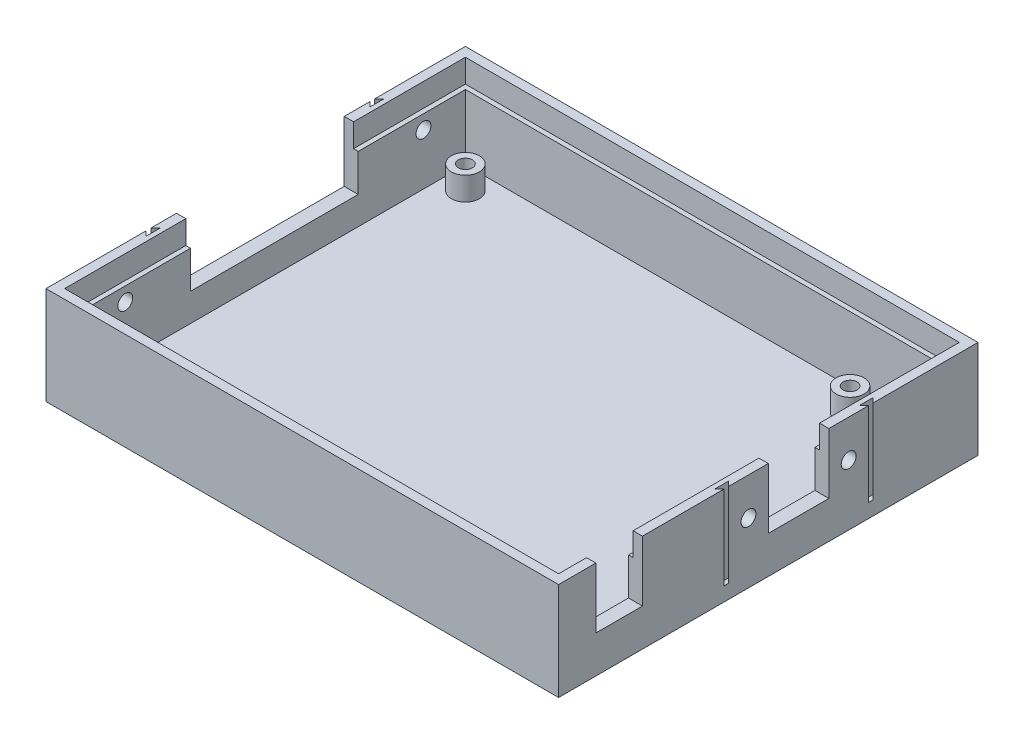
SolidWorks part; units mm, degrees
ref_plane "Alzado" through (0, 0, 0) normal (0, 0, 1) x (1, 0, 0)
ref_plane "Planta" through (0, 0, 0) normal (0, 1, 0) x (1, 0, 0)
ref_plane "Vista lateral" through (0, 0, 0) normal (1, 0, 0) x (0, 0, -1)
sketch "Croquis1" plane through (0, 0, 0) normal (0, 1, 0) x (1, 0, 0)
  line L1 (-51, -41) -> (51, -41) construction
  line L2 (-51, -41) -> (-51, 41) construction
  line L3 (-51, 41) -> (51, 41) construction
  line L4 (51, -41) -> (51, 41) construction
  line L5 (-51, -41) -> (51, 41) construction
  line L6 (-51, 41) -> (51, -41) construction
  line L7 (-55, -45) -> (55, -45)
  line L8 (-55, -45) -> (-55, 45)
  line L9 (-55, 45) -> (55, 45)
  line L10 (55, -45) -> (55, 45)
  line L11 (-55, -45) -> (55, 45) construction
  line L12 (-55, 45) -> (55, -45) construction
  point P0 (0, 0)
  point P6 (0, 0)
  dimension "D1" = 82
  dimension "D2" = 102
  dimension "D3" = 4
  dimension "D4" = 4
extrude "Saliente-Extruir1" add sketch "Croquis1" along normal blind 2
sketch "Croquis3" plane through (0, 2, 0) normal (0, 1, 0) x (1, 0, 0)
  line L0 (0, 0) -> (-51, 0) construction
  line L1 (-51, -41) -> (51, -41) construction
  line L2 (-51, -41) -> (-51, 41) construction
  line L3 (-51, 41) -> (51, 41) construction
  line L4 (51, -41) -> (51, 41) construction
  line L5 (-51, -41) -> (51, 41) construction
  line L6 (-51, 41) -> (51, -41) construction
  circle A0 centre (-47.19, -37.19) radius 3
  circle A1 centre (-47.19, 37.19) radius 3
  circle A2 centre (35.36, -37.19) radius 3
  circle A3 centre (35.36, 37.19) radius 3
  point P0 (0, 0)
  dimension "D3" = 6
  dimension "D4" = 3.81
  dimension "D5" = 3.81
  dimension "D6" = 6
  dimension "D7" = 86.36
  dimension "D8" = 3.81
  dimension "D1" = 82
  dimension "D2" = 102
extrude "Saliente-Extruir2" add sketch "Croquis3" along normal blind 5
sketch "Croquis4" plane through (0, 7, 0) normal (0, 1, 0) x (1, 0, 0)
  circle A0 centre (-47.19, -37.19) radius 1.5
  circle A1 centre (35.36, -37.19) radius 1.5
  circle A2 centre (35.36, 37.19) radius 1.5
  circle A3 centre (-47.19, 37.19) radius 1.5
  dimension "D1" = 3
  dimension "D2" = 3
  dimension "D3" = 3
  dimension "D4" = 3
extrude "Cortar-Extruir1" cut sketch "Croquis4" against normal blind 4
sketch "Croquis5" plane through (0, 2, 0) normal (0, 1, 0) x (1, 0, 0)
  line L0 (52, -37) -> (55, -37)
  line L1 (-55, -45) -> (55, -45)
  line L2 (-55, -45) -> (-55, -17)
  line L3 (-55, 45) -> (55, 45)
  line L4 (55, -45) -> (55, -37)
  line L5 (-55, -45) -> (55, 45) construction
  line L6 (-55, 45) -> (55, -45) construction
  line L7 (-52, -42) -> (52, -42)
  line L8 (-52, -42) -> (-52, -17)
  line L9 (-52, 42) -> (52, 42)
  line L10 (52, -42) -> (52, -37)
  line L11 (-52, -42) -> (52, 42) construction
  line L12 (-52, 42) -> (52, -42) construction
  line L13 (52, -27) -> (55, -27)
  line L14 (52, 13) -> (55, 13)
  line L15 (52, 0) -> (55, 0)
  line L16 (52, 13) -> (52, 42)
  line L17 (55, 13) -> (55, 45)
  line L18 (52, -27) -> (52, 0)
  line L19 (55, -27) -> (55, 0)
  line L20 (-52, -17) -> (-55, -17)
  line L21 (-55, 19) -> (-52, 19)
  line L22 (-52, 19) -> (-52, 42)
  line L23 (-55, 19) -> (-55, 45)
  point P0 (0, 0)
  point P7 (0, 0)
  dimension "D1" = 3
  dimension "D2" = 3
  dimension "D3" = 5
  dimension "D4" = 15
  dimension "D5" = 42
  dimension "D6" = 55
  dimension "D7" = 25
  dimension "D8" = 61
extrude "Saliente-Extruir3" add sketch "Croquis5" along normal blind 19
sketch "Croquis6" plane through (0, 2, 0) normal (0, 1, 0) x (1, 0, 0)
  line L0 (55, -27) -> (55, 0) construction
  line L1 (-52, 19) -> (-55, 19)
  line L2 (-52, 19) -> (-52, -17)
  line L3 (-52, -17) -> (-55, -17)
  line L4 (-55, 19) -> (-55, -17)
  line L5 (52, 13) -> (55, 13)
  line L6 (52, 13) -> (52, 0)
  line L7 (52, 0) -> (55, 0)
  line L8 (55, 13) -> (55, 0)
  line L9 (55, 0) -> (52, 0) construction
  line L11 (52, -27) -> (55, -27)
  line L12 (52, -27) -> (52, -37)
  line L13 (52, -37) -> (55, -37)
  line L14 (55, -27) -> (55, -37)
extrude "Saliente-Extruir4" add sketch "Croquis6" along normal blind 6
sketch "Croquis7" plane through (0, 21, 0) normal (0, 1, 0) x (1, 0, 0)
  line L0 (-53, -43) -> (-53, 43)
  line L1 (-52, -42) -> (52, -42)
  line L2 (-52, -42) -> (-52, 42)
  line L3 (-52, 42) -> (52, 42)
  line L4 (52, -42) -> (52, 42)
  line L5 (-53, 43) -> (53, 43)
  line L6 (53, -43) -> (53, 43)
  line L7 (-53, -43) -> (53, -43)
  dimension "D1" = 1
extrude "Cortar-Extruir2" cut sketch "Croquis7" against normal blind 5
sketch "Croquis8" plane through (0, 21, 0) normal (0, 1, 0) x (1, 0, 0)
  line L0 (55, -27) -> (55, 0) construction
  line L1 (55, -8.5) -> (54, -7.5)
  line L2 (54, -7.5) -> (54, -10.5)
  line L3 (54, -10.5) -> (55, -9.5)
  line L4 (55, -9.5) -> (55, -8.5)
  line L5 (54, -9) -> (55, -9) construction
  line L6 (52, 0) -> (55, 0) construction
  line L7 (55, 6.5) -> (52, 6.5) construction
  line L8 (55, 0) -> (55, 13) construction
  line L9 (52, 42) -> (52, -42) construction
  line L10 (54, 22) -> (55, 22) construction
  line L11 (55, 22.5) -> (55, 21.5)
  line L12 (54, 23.5) -> (55, 22.5)
  line L13 (54, 20.5) -> (54, 23.5)
  line L14 (55, 21.5) -> (54, 20.5)
  point P5 (54, -9)
  dimension "D1" = 1
  dimension "D2" = 1
  dimension "D3" = 45
  dimension "D4" = 9
extrude "Cortar-Extruir3" cut sketch "Croquis8" against normal blind 18
sketch "Croquis9" plane through (55, 0, 0) normal (1, 0, 0) x (0, 0, -1)
  line L0 (-8.5, 21) -> (0, 21) construction
  line L1 (-4.25, 13) -> (-4.25, 21) construction
  line L2 (6.5, 8) -> (6.5, 15) construction
  line L3 (0, 8) -> (13, 8) construction
  circle A0 centre (-4.25, 13) radius 1.6
  circle A1 centre (17.25, 13) radius 1.6
  dimension "D1" = 3.2
  dimension "D2" = 8
  dimension "D3" = 10.75
extrude "Cortar-Extruir4" cut sketch "Croquis9" against normal blind 12
sketch "Croquis11" plane through (0, 21, 0) normal (0, 1, 0) x (1, 0, 0)
  line L0 (-55, -22.5) -> (-54, -21.5)
  line L1 (-55, -17) -> (-55, -45) construction
  line L2 (-54, -21.5) -> (-54, -24.5)
  line L3 (-54, -24.5) -> (-55, -23.5)
  line L4 (-55, -23.5) -> (-55, -22.5)
  line L5 (-55, -23) -> (-54, -23) construction
  line L6 (-55, 1) -> (-52, 1) construction
  line L7 (-55, 19) -> (-55, -17) construction
  line L8 (-52, -17) -> (-52, 19) construction
  line L9 (-55, -17) -> (-52, -17) construction
  line L10 (-55, 25) -> (-54, 25) construction
  line L11 (-55, 25.5) -> (-55, 24.5)
  line L12 (-54, 26.5) -> (-55, 25.5)
  line L13 (-54, 23.5) -> (-54, 26.5)
  line L14 (-55, 24.5) -> (-54, 23.5)
  dimension "D1" = 1
  dimension "D2" = 1
  dimension "D3" = 45
  dimension "D4" = 45
  dimension "D5" = 6
extrude "Cortar-Extruir5" cut sketch "Croquis11" against normal blind 18
sketch "Croquis13" plane through (55, 0, 0) normal (1, 0, 0) x (0, 0, -1)
  line L1 (-9.5, 3) -> (-9.5, 18.9094) construction
  line L2 (22.5, 3) -> (22.5, 18.9094) construction
  dimension "D1" = 32
sketch "Croquis14" plane through (-55, 0, 0) normal (-1, 0, 0) x (0, 0, 1)
  line L0 (-45, 21) -> (-25.5, 21) construction
  line L1 (-1, 8) -> (-1, 28.6536) construction
  line L2 (-19, 8) -> (17, 8) construction
  circle A0 centre (-33, 13) radius 1.6
  circle A2 centre (31, 13) radius 1.6
  dimension "D1" = 3.2
  dimension "D2" = 8
  dimension "D3" = 32
extrude "Cortar-Extruir6" cut sketch "Croquis14" against normal blind 10
equation "\"D2@Croquis4\"=\"D1@Croquis4\""
equation "\"D3@Croquis4\"=\"D1@Croquis4\""
equation "\"D4@Croquis4\"=\"D1@Croquis4\""
